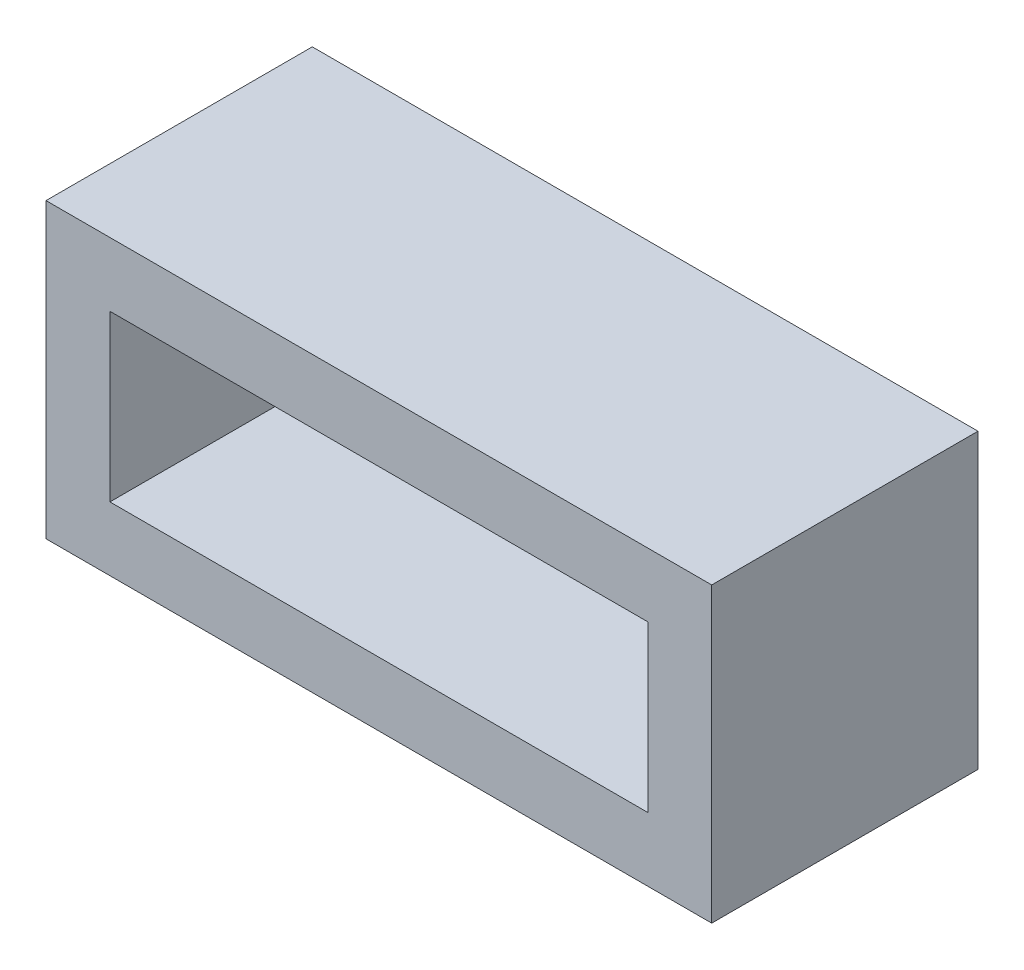
SolidWorks part; units mm, degrees
ref_plane "Front Plane" through (0, 0, 0) normal (0, 0, 1) x (1, 0, 0)
ref_plane "Top Plane" through (0, 0, 0) normal (0, 1, 0) x (1, 0, 0)
ref_plane "Right Plane" through (0, 0, 0) normal (1, 0, 0) x (0, 0, -1)
sketch "Sketch1" plane through (0, 0, 0) normal (0, 0, 1) x (1, 0, 0)
  line L1 (-10.1, -3.1) -> (10.1, -3.1)
  line L2 (-10.1, -3.1) -> (-10.1, 3.1)
  line L3 (-10.1, 3.1) -> (10.1, 3.1)
  line L4 (10.1, -3.1) -> (10.1, 3.1)
  line L5 (-10.1, -3.1) -> (10.1, 3.1) construction
  line L6 (-10.1, 3.1) -> (10.1, -3.1) construction
  line L7 (-12.5, -5.5) -> (12.5, -5.5)
  line L8 (-12.5, -5.5) -> (-12.5, 5.5)
  line L9 (-12.5, 5.5) -> (12.5, 5.5)
  line L10 (12.5, -5.5) -> (12.5, 5.5)
  line L11 (-12.5, -5.5) -> (12.5, 5.5) construction
  line L12 (-12.5, 5.5) -> (12.5, -5.5) construction
  point P0 (0, 0)
  point P6 (0, 0)
  dimension "D1" = 20.2
  dimension "D2" = 6.2
  dimension "D3" = 25
  dimension "D4" = 11
extrude "Boss-Extrude1" add sketch "Sketch1" along normal blind 10
